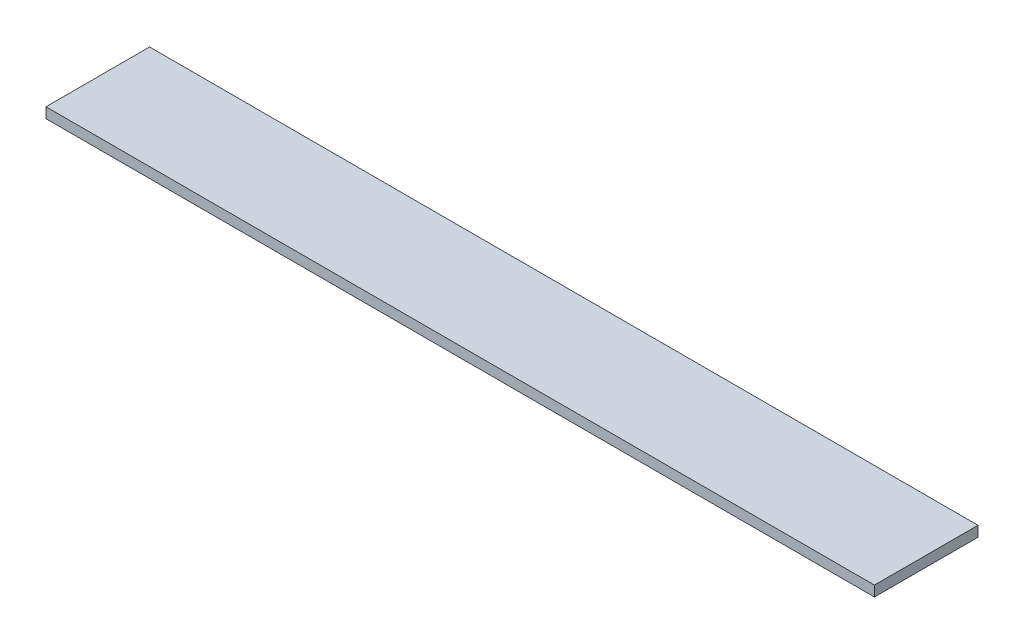
SolidWorks part; units mm, degrees
ref_plane "Front Plane" through (0, 0, 0) normal (0, 0, 1) x (1, 0, 0)
ref_plane "Top Plane" through (0, 0, 0) normal (0, 1, 0) x (1, 0, 0)
ref_plane "Right Plane" through (0, 0, 0) normal (1, 0, 0) x (0, 0, -1)
sketch "Sketch1" plane through (0, 0, 0) normal (0, 1, 0) x (1, 0, 0)
  line L1 (0, 0) -> (203.2, 0)
  line L2 (0, 0) -> (0, 25.4)
  line L3 (0, 25.4) -> (203.2, 25.4)
  line L4 (203.2, 0) -> (203.2, 25.4)
  dimension "D1" = 25.4
  dimension "D2" = 203.2
extrude "Boss-Extrude1" add sketch "Sketch1" along normal blind 2.54
